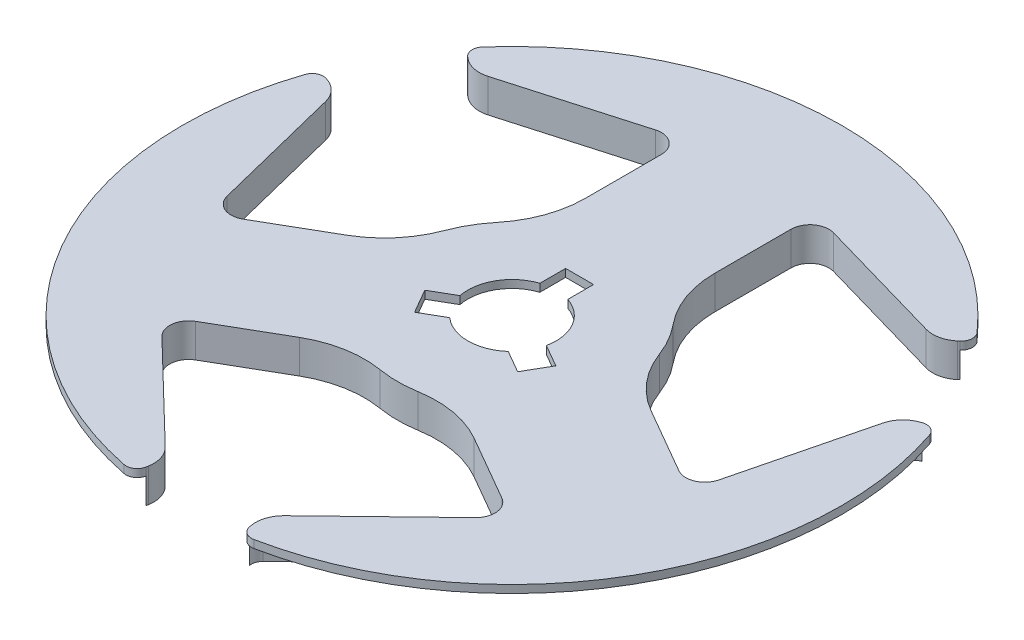
SolidWorks part; units mm, degrees
material "Nylon 6/10"
ref_plane "Front Plane" through (0, 0, 0) normal (0, 0, 1) x (1, 0, 0)
ref_plane "Top Plane" through (0, 0, 0) normal (0, 1, 0) x (1, 0, 0)
ref_plane "Right Plane" through (0, 0, 0) normal (1, 0, 0) x (0, 0, -1)
sketch "Sketch1" plane through (0, 0, 0) normal (0, 1, 0) x (1, 0, 0)
  line L0 (-1.27, 4.8706) -> (-1.27, 2.0368)
  line L1 (1.27, 4.8706) -> (1.27, 2.0368)
  line L2 (-5.3631, 4.5396) -> (-2.08, 5.481)
  line L3 (2.08, 5.481) -> (5.3631, 4.5396)
  arc A0 (5.6238, 4.9516) -> (-5.6238, 4.9516) centre (0, 0) ccw
  circle A1 centre (0, 0) radius 2.4003
  arc A2 (-2.08, 5.481) -> (-1.27, 4.8706) centre (-1.905, 4.8706) cw
  arc A3 (1.27, 4.8706) -> (2.08, 5.481) centre (1.905, 4.8706) cw
  arc A4 (-5.6238, 4.9516) -> (-5.3631, 4.5396) centre (-5.4331, 4.7837) ccw
  arc A5 (5.6238, 4.9516) -> (5.3631, 4.5396) centre (5.4331, 4.7837) cw
  dimension "D1" = 14.986
  dimension "D6" = 4.8006
  dimension "D9" = 0.635
  dimension "D10" = 0.254
  dimension "D2" = 74
  dimension "D3" = 74
  dimension "D4" = 2.54
  dimension "D5" = 1.27
  dimension "D7" = 5.842
  dimension "D8" = 5.842
extrude "Boss-Extrude1" add sketch "Sketch1" along normal blind 0.1778 contours A5 A0 A4 L2 A2 L0 A1 L1 A3 L3 | A1
pattern_circular "CirPattern1" count 3 over 360 about axis through (0, 0, 0) along (0, 1, 0) of "Boss-Extrude1"
sketch "Sketch2" plane through (0, 0.1778, 0) normal (0, 1, 0) x (1, 0, 0)
  line L0 (0.3175, 1.5367) -> (-0.3175, 1.5367)
  line L1 (-0.3175, 1.5367) -> (-0.3175, 0.9517)
  line L2 (0.3175, 1.5367) -> (0.3175, 0.9517)
  circle A0 centre (0, 0) radius 1.0033
  dimension "D4" = 2.0066
  dimension "D1" = 0.635
  dimension "D2" = 0.3175
  dimension "D3" = 2.54
extrude "Cut-Extrude3" cut sketch "Sketch2" along direction (0, -1, 0) on the side against the normal through all contours A0 | A0 L2 L0 L1
pattern_circular "CirPattern2" count 3 over 360 about axis through (0, 0, 0) along (0, 1, 0) of "Cut-Extrude3"
fillet "Fillet1" radius 2.54 6 edges at (-1.27, 0.0889, -2.0368) (-2.3989, 0.0889, -0.0815) (-1.1289, 0.0889, 2.1183) (1.1289, 0.0889, 2.1183) (2.3989, 0.0889, -0.0815) (1.27, 0.0889, -2.0368)
sketch "Sketch3" plane through (0, 0.1778, 0) normal (0, 1, 0) x (1, 0, 0)
  line L2 (-5.3071, 4.3442) -> (-2.024, 5.2857)
  line L3 (-4.9808, 4.4378) -> (-2.024, 5.2857)
  line L14 (-5.5662, 4.5636) -> (-5.5973, 4.5899)
  line L15 (-6.7352, 2.5387) -> (-6.7736, 2.5524)
  line L17 (-5.5895, -0.89) -> (-6.4158, 2.424)
  line L18 (-3.4602, -0.2966) -> (-4.9547, -1.1595)
  line L19 (-1.4732, 4.8706) -> (-1.4732, 3.1449)
  line L20 (-5.5895, -0.89) -> (-6.3337, 2.0946)
  line L21 (-3.4602, -0.2966) -> (-4.9547, -1.1595)
  line L22 (-1.4732, 4.8706) -> (-1.4732, 3.1449)
  line L34 (4.8531, -1.3354) -> (3.3586, -0.4726)
  line L35 (1.27, 3.1449) -> (1.27, 4.8706)
  line L36 (2.08, 5.481) -> (5.3631, 4.5396)
  line L37 (-5.3631, 4.5396) -> (-2.08, 5.481)
  line L38 (-1.27, 4.8706) -> (-1.27, 3.1449)
  line L39 (-3.3586, -0.4726) -> (-4.8531, -1.3354)
  line L40 (-5.7867, -0.9391) -> (-6.613, 2.3748)
  line L41 (-1.2498, -6.9144) -> (-3.7067, -4.5419)
  line L42 (-3.5831, -3.5351) -> (-2.0886, -2.6723)
  line L43 (2.0886, -2.6723) -> (3.5831, -3.5351)
  line L44 (3.7067, -4.5419) -> (1.2498, -6.9144)
  line L45 (6.613, 2.3748) -> (5.7867, -0.9391)
  line L49 (-5.3631, 4.5396) -> (-2.08, 5.481)
  line L50 (-1.27, 4.8706) -> (-1.27, 3.1449)
  line L51 (-3.3586, -0.4726) -> (-4.8531, -1.3354)
  line L52 (-5.7867, -0.9391) -> (-6.613, 2.3748)
  arc A25 (-5.6238, 4.9516) -> (-5.3631, 4.5396) centre (-5.4331, 4.7837) ccw construction
  arc A26 (-6.613, 2.3748) -> (-7.1001, 2.3945) centre (-6.8594, 2.3134) ccw construction
  arc A27 (-5.5662, 4.5636) -> (-4.9808, 4.4378) centre (-5.1559, 5.0482) ccw
  arc A28 (-6.3337, 2.0946) -> (-6.7352, 2.5387) centre (-6.9498, 1.941) ccw
  arc A30 (-5.5895, -0.89) -> (-4.9547, -1.1595) centre (-5.1706, -0.7855) ccw
  arc A31 (-3.4602, -0.2966) -> (-2.4392, 0.9102) centre (-4.6286, 1.7271) ccw
  arc A32 (-2.0078, 1.6573) -> (-2.4392, 0.9102) centre (0, 0) ccw
  arc A33 (-2.0078, 1.6573) -> (-1.4732, 3.1449) centre (-3.81, 3.1449) ccw
  arc A34 (-1.4732, 4.8706) -> (-2.024, 5.2857) centre (-1.905, 4.8706) ccw
  arc A35 (-5.5895, -0.89) -> (-4.9547, -1.1595) centre (-5.1706, -0.7855) ccw
  arc A36 (-3.4602, -0.2966) -> (-2.4392, 0.9102) centre (-4.6286, 1.7271) ccw
  arc A37 (-2.0078, 1.6573) -> (-2.4392, 0.9102) centre (0, 0) ccw
  arc A38 (-2.0078, 1.6573) -> (-1.4732, 3.1449) centre (-3.81, 3.1449) ccw
  arc A39 (-1.4732, 4.8706) -> (-2.024, 5.2857) centre (-1.905, 4.8706) ccw
  arc A63 (2.2488, 0.8391) -> (3.3586, -0.4726) centre (4.6286, 1.7271) ccw
  arc A64 (2.2488, 0.8391) -> (1.8511, 1.528) centre (0, 0) ccw
  arc A65 (1.27, 3.1449) -> (1.8511, 1.528) centre (3.81, 3.1449) ccw
  arc A66 (2.08, 5.481) -> (1.27, 4.8706) centre (1.905, 4.8706) ccw
  arc A67 (5.3631, 4.5396) -> (5.6238, 4.9516) centre (5.4331, 4.7837) ccw
  arc A68 (5.6238, 4.9516) -> (-5.6238, 4.9516) centre (0, 0) ccw
  arc A69 (-5.6238, 4.9516) -> (-5.3631, 4.5396) centre (-5.4331, 4.7837) ccw
  arc A70 (-1.27, 4.8706) -> (-2.08, 5.481) centre (-1.905, 4.8706) ccw
  arc A71 (-1.8511, 1.528) -> (-1.27, 3.1449) centre (-3.81, 3.1449) ccw
  arc A72 (-1.8511, 1.528) -> (-2.2488, 0.8391) centre (0, 0) ccw
  arc A73 (-3.3586, -0.4726) -> (-2.2488, 0.8391) centre (-4.6286, 1.7271) ccw
  arc A74 (-5.7867, -0.9391) -> (-4.8531, -1.3354) centre (-5.1706, -0.7855) ccw
  arc A75 (-6.613, 2.3748) -> (-7.1001, 2.3945) centre (-6.8594, 2.3134) ccw
  arc A76 (-7.1001, 2.3945) -> (-1.4763, -7.3461) centre (0, 0) ccw
  arc A77 (-1.4763, -7.3461) -> (-1.2498, -6.9144) centre (-1.4263, -7.0971) ccw
  arc A78 (-3.5831, -3.5351) -> (-3.7067, -4.5419) centre (-3.2656, -4.0851) ccw
  arc A79 (-0.3977, -2.3671) -> (-2.0886, -2.6723) centre (-0.8186, -4.872) ccw
  arc A80 (-0.3977, -2.3671) -> (0.3977, -2.3671) centre (0, 0) ccw
  arc A81 (2.0886, -2.6723) -> (0.3977, -2.3671) centre (0.8186, -4.872) ccw
  arc A82 (3.7067, -4.5419) -> (3.5831, -3.5351) centre (3.2656, -4.0851) ccw
  arc A83 (1.2498, -6.9144) -> (1.4763, -7.3461) centre (1.4263, -7.0971) ccw
  arc A84 (1.4763, -7.3461) -> (7.1001, 2.3945) centre (0, 0) ccw
  arc A85 (7.1001, 2.3945) -> (6.613, 2.3748) centre (6.8594, 2.3134) ccw
  arc A86 (4.8531, -1.3354) -> (5.7867, -0.9391) centre (5.1706, -0.7855) ccw
  arc A93 (-5.5973, 4.5899) -> (-5.3631, 4.5396) centre (-5.4331, 4.7837) ccw
  arc A94 (-1.27, 4.8706) -> (-2.08, 5.481) centre (-1.905, 4.8706) ccw
  arc A95 (-1.8511, 1.528) -> (-1.27, 3.1449) centre (-3.81, 3.1449) ccw
  arc A96 (-1.8511, 1.528) -> (-2.2488, 0.8391) centre (0, 0) ccw
  arc A97 (-3.3586, -0.4726) -> (-2.2488, 0.8391) centre (-4.6286, 1.7271) ccw
  arc A98 (-5.7867, -0.9391) -> (-4.8531, -1.3354) centre (-5.1706, -0.7855) ccw
  arc A99 (-6.613, 2.3748) -> (-6.7736, 2.5524) centre (-6.8594, 2.3134) ccw
  dimension "D3" = 0.635
  dimension "D1" = 0.2032
  dimension "D2" = 0.2032
  dimension "D4" = 0
extrude "Boss-Extrude2" add sketch "Sketch3" against normal blind 0.762
pattern_circular "CirPattern3" count 3 over 360 about axis through (0, 0, 0) along (0, 1, 0) of "Boss-Extrude2"
